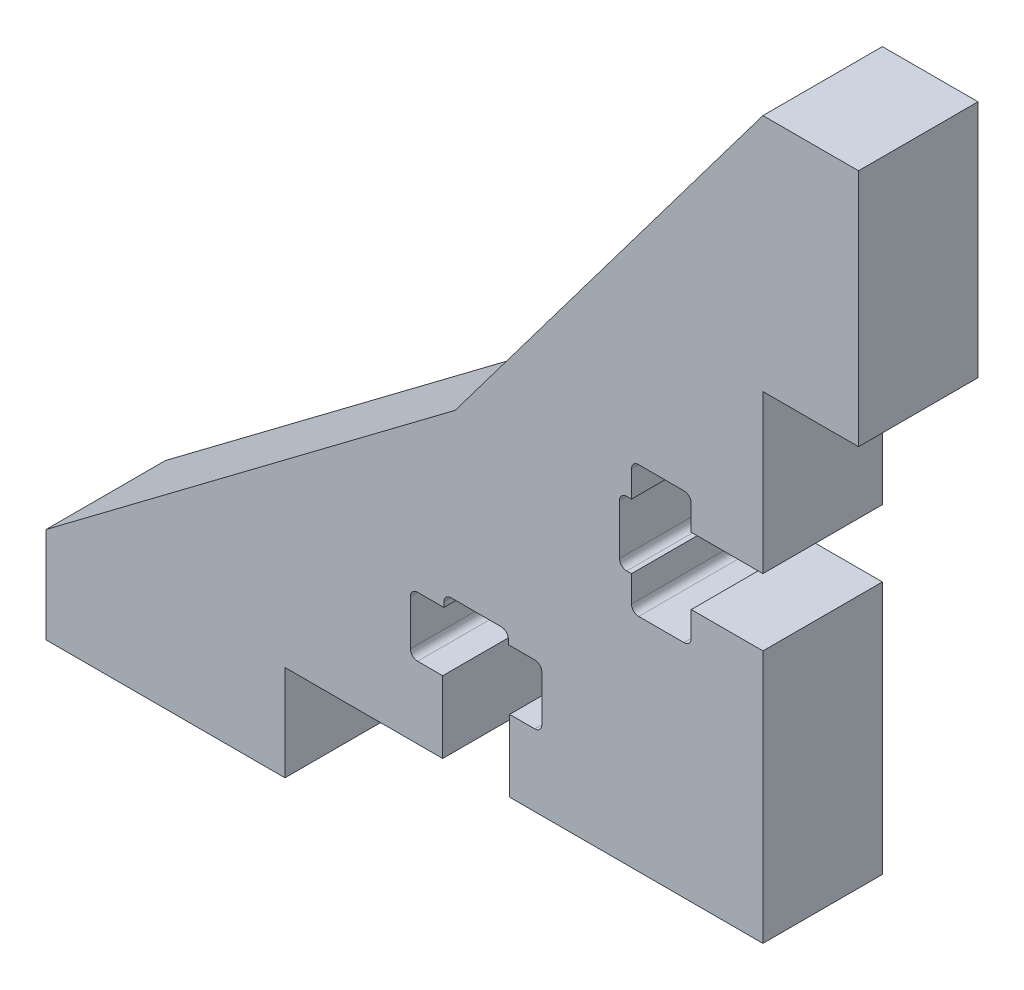
SolidWorks part; units mm, degrees
ref_plane "前视基准面" through (0, 0, 0) normal (0, 0, 1) x (1, 0, 0)
ref_plane "上视基准面" through (0, 0, 0) normal (0, 1, 0) x (1, 0, 0)
ref_plane "右视基准面" through (0, 0, 0) normal (1, 0, 0) x (0, 0, -1)
sketch "草图1" plane through (0, 0, 0) normal (0, 0, 1) x (1, 0, 0)
  line L0 (0, 0) -> (30, 0)
  line L1 (30, 0) -> (30, 30)
  line L2 (30, 30) -> (0, 0)
extrude "凸台-拉伸1" add sketch "草图1" along normal blind 5
sketch "草图2" plane through (0, 0, 5) normal (0, 0, 1) x (1, 0, 0)
  line L0 (30, 30) -> (0, 0) construction
  line L1 (30, 30) -> (0, 0)
  line L2 (15, 15) -> (17.1213, 12.8787)
  line L3 (17.1213, 12.8787) -> (0, 0)
  line L4 (30, 30) -> (17.1213, 12.8787)
  line M1 (30, 30) -> (0, 0)
extrude "切除-拉伸1" cut sketch "草图2" against normal blind 10 contours L3 L2 L1 | L4 L2 M1
sketch "草图3" plane through (0, 0, 0) normal (0, -1, 0) x (1, 0, 0)
  line L0 (0, 0) -> (10, 0)
  line L1 (10, 0) -> (10, 5)
  line L4 (0, 0) -> (30, 0)
  line L5 (30, 0) -> (30, 5)
  line L6 (30, 5) -> (0, 5)
  line L7 (0, 5) -> (0, 0)
  line L8 (0, 0) -> (10, 0)
  line L9 (30, 0) -> (30, 5)
  line L10 (10, 5) -> (0, 5)
  line L11 (0, 5) -> (0, 0)
  line M5 (0, 0) -> (30, 0)
  line M7 (30, 5) -> (0, 5)
  line M8 (0, 5) -> (0, 0)
  dimension "D1" = 0
extrude "凸台-拉伸2" add sketch "草图3" along normal blind 5 contours L1 M5 M7 M8
sketch "草图4" plane through (30, 0, 0) normal (1, 0, 0) x (0, 0, -1)
  line L0 (0, 30) -> (0, 20)
  line L1 (0, 20) -> (-5, 20)
  line L2 (-5, 20) -> (-5, 30)
  line L4 (0, 0) -> (0, 30)
  line L5 (0, 30) -> (-5, 30)
  line L6 (-5, 30) -> (-5, 0)
  line L7 (-5, 0) -> (0, 0)
  line L8 (0, 0) -> (0, 30)
  line L9 (0, 30) -> (-5, 30)
  line L10 (-5, 30) -> (-5, 0)
  line L11 (-5, 0) -> (0, 0)
  line M5 (0, 0) -> (0, 30)
  line M6 (0, 30) -> (-5, 30)
  line M7 (-5, 30) -> (-5, 0)
  dimension "D1" = 0
extrude "凸台-拉伸3" add sketch "草图4" along normal blind 5 contours L1 M5 M6 M7
sketch "草图5" plane through (0, -5, 0) normal (0, -1, 0) x (1, 0, 0)
  line L4 (0, 0) -> (10, 0)
  line L5 (10, 0) -> (10, 5)
  line L6 (10, 5) -> (0, 5)
  line L7 (0, 5) -> (0, 0)
  line L8 (0, 0) -> (10, 0)
  line L9 (10, 0) -> (10, 5)
  line L10 (10, 5) -> (0, 5)
  line L11 (0, 5) -> (0, 0)
  dimension "D1" = 0
extrude "切除-拉伸2" cut sketch "草图5" against normal blind 1
sketch "草图6" plane through (35, 0, 0) normal (1, 0, 0) x (0, 0, -1)
  line L4 (-5, 20) -> (0, 20)
  line L5 (0, 20) -> (0, 30)
  line L6 (0, 30) -> (-5, 30)
  line L7 (-5, 30) -> (-5, 20)
  line L8 (-5, 20) -> (0, 20)
  line L9 (0, 20) -> (0, 30)
  line L10 (0, 30) -> (-5, 30)
  line L11 (-5, 30) -> (-5, 20)
  dimension "D1" = 0
extrude "切除-拉伸3" cut sketch "草图6" against normal blind 1
extrude "切除-拉伸5" cut sketch "草图8" against normal blind 5
sketch "草图8" plane through (-129.7231, 239.9432, 0) normal (0, 0, -1) x (0, 1, 0)
  line L1 (-229.3432, 156.7231) -> (-229.3432, 159.2231)
  line L3 (-230.3932, 156.7231) -> (-229.3432, 156.7231)
  line L5 (-230.6932, 154.5231) -> (-230.6932, 156.4231)
  line L7 (-229.2932, 154.2231) -> (-230.3932, 154.2231)
  line L9 (-229.2932, 154.0231) -> (-229.2932, 154.2231)
  line L11 (-226.8932, 153.7231) -> (-228.9932, 153.7231)
  line L13 (-226.5932, 154.2231) -> (-226.5932, 154.0231)
  line L15 (-225.4932, 154.2231) -> (-226.5932, 154.2231)
  line L17 (-225.1932, 156.4231) -> (-225.1932, 154.5231)
  line L19 (-226.5432, 156.7231) -> (-225.4932, 156.7231)
  line L21 (-226.5432, 159.2231) -> (-226.5432, 156.7231)
  line L22 (-229.3432, 159.2231) -> (-229.3432, 161.2231)
  line L23 (-229.3432, 161.2231) -> (-226.5432, 161.2231)
  line L24 (-226.5432, 161.2231) -> (-226.5432, 159.2231)
  line L26 (-239.4432, 149.1231) -> (-236.9432, 149.1231)
  line L28 (-236.9432, 146.3231) -> (-239.4432, 146.3231)
  line L30 (-236.9432, 149.1231) -> (-236.9432, 150.1731)
  line L32 (-236.6432, 150.4731) -> (-234.7432, 150.4731)
  line L34 (-234.4432, 150.1731) -> (-234.4432, 149.0731)
  line L36 (-234.4432, 149.0731) -> (-234.2432, 149.0731)
  line L38 (-233.9432, 148.7731) -> (-233.9432, 146.6731)
  line L40 (-234.2432, 146.3731) -> (-234.4432, 146.3731)
  line L42 (-234.4432, 146.3731) -> (-234.4432, 145.2731)
  line L44 (-234.7432, 144.9731) -> (-236.6432, 144.9731)
  line L46 (-236.9432, 145.2731) -> (-236.9432, 146.3231)
  line L47 (-239.4432, 149.1231) -> (-241.4432, 149.1231)
  line L48 (-241.4432, 149.1231) -> (-241.4432, 146.3231)
  line L49 (-241.4432, 146.3231) -> (-239.4432, 146.3231)
  arc A1 (-230.3932, 156.7231) -> (-230.6932, 156.4231) centre (-230.3932, 156.4231) ccw
  arc A3 (-230.6932, 154.5231) -> (-230.3932, 154.2231) centre (-230.3932, 154.5231) ccw
  arc A5 (-229.2932, 154.0231) -> (-228.9932, 153.7231) centre (-228.9932, 154.0231) ccw
  arc A7 (-226.8932, 153.7231) -> (-226.5932, 154.0231) centre (-226.8932, 154.0231) ccw
  arc A9 (-225.4932, 154.2231) -> (-225.1932, 154.5231) centre (-225.4932, 154.5231) ccw
  arc A11 (-225.1932, 156.4231) -> (-225.4932, 156.7231) centre (-225.4932, 156.4231) ccw
  arc A13 (-236.6432, 150.4731) -> (-236.9432, 150.1731) centre (-236.6432, 150.1731) ccw
  arc A15 (-234.4432, 150.1731) -> (-234.7432, 150.4731) centre (-234.7432, 150.1731) ccw
  arc A17 (-233.9432, 148.7731) -> (-234.2432, 149.0731) centre (-234.2432, 148.7731) ccw
  arc A19 (-234.2432, 146.3731) -> (-233.9432, 146.6731) centre (-234.2432, 146.6731) ccw
  arc A21 (-234.7432, 144.9731) -> (-234.4432, 145.2731) centre (-234.7432, 145.2731) ccw
  arc A23 (-236.9432, 145.2731) -> (-236.6432, 144.9731) centre (-236.6432, 145.2731) ccw
